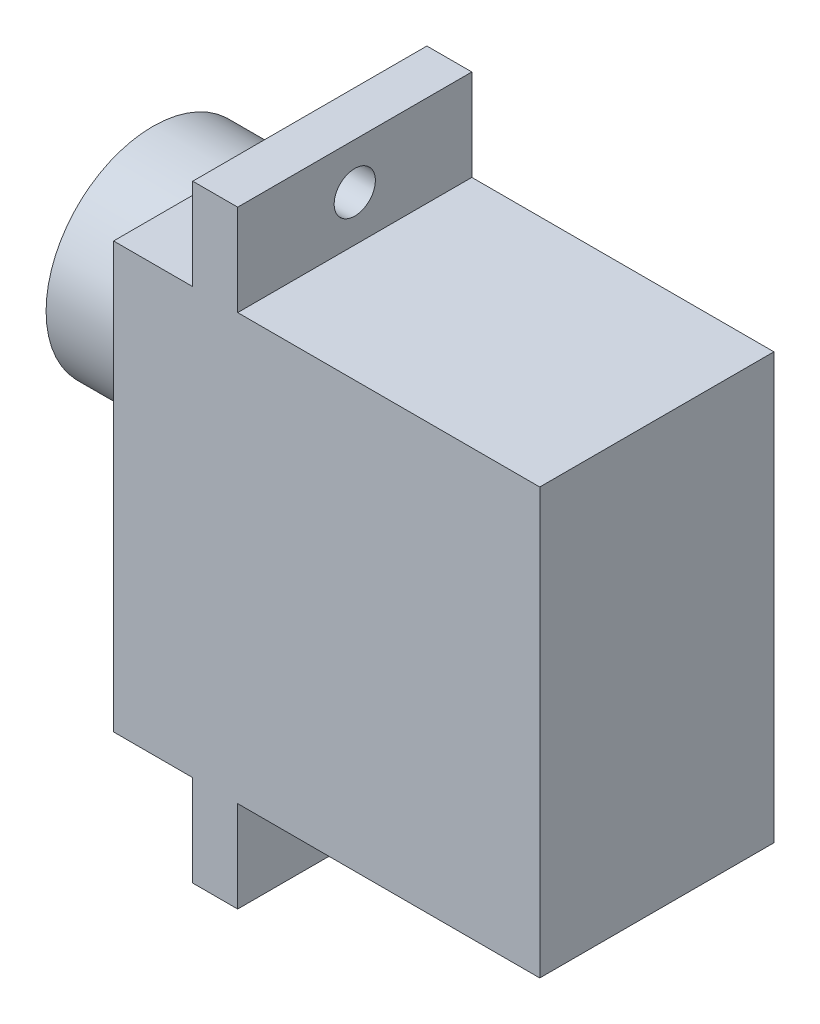
SolidWorks part; units mm, degrees
ref_plane "Front Plane" through (0, 0, 0) normal (0, 0, 1) x (1, 0, 0)
ref_plane "Top Plane" through (0, 0, 0) normal (0, 1, 0) x (1, 0, 0)
ref_plane "Right Plane" through (0, 0, 0) normal (1, 0, 0) x (0, 0, -1)
sketch "Sketch1" plane through (0, 0, 0) normal (0, 0, 1) x (1, 0, 0)
  line L1 (11.375, -11.35) -> (-11.375, -11.35)
  line L2 (11.375, -11.35) -> (11.375, 11.35)
  line L3 (11.375, 11.35) -> (-11.375, 11.35)
  line L4 (-11.375, -11.35) -> (-11.375, 11.35)
  line L5 (11.375, -11.35) -> (-11.375, 11.35) construction
  line L6 (11.375, 11.35) -> (-11.375, -11.35) construction
  point P0 (0, 0)
  dimension "D1" = 22.75
  dimension "D2" = 22.7
extrude "Boss-Extrude1" add sketch "Sketch1" along normal blind 12.5
sketch "Sketch2" plane through (-11.375, 0, 0) normal (-1, 0, 0) x (0, 0, 1)
  line L0 (6.153, 11.8112) -> (6.153, -12.8337) construction
  line L1 (12.5, 11.35) -> (0, 11.35) construction
  circle A0 centre (6.153, 5.65) radius 5.7
  dimension "D1" = 11.4
extrude "Boss-Extrude2" add sketch "Sketch2" along normal blind 4.25
sketch "Sketch3" plane through (-15.625, 0, 0) normal (-1, 0, 0) x (0, 0, 1)
  circle A0 centre (6.153, 5.65) radius 2.3
  dimension "D1" = 4.6
extrude "Cut-Extrude1" cut sketch "Sketch3" against normal blind 2
ref_plane "Plane1" through (11.35, 0, 0) normal (1, 0, 0) x (0, 0, -1)
ref_plane "Plane2" through (-7.15, 0, 0) normal (1, 0, 0) x (0, 0, -1)
sketch "Sketch4" plane through (-7.15, 0, 0) normal (1, 0, 0) x (0, 0, -1)
  line L0 (4.1399, 0) -> (-19.2617, 0) construction
  line L1 (-12.5, 11.35) -> (0, 11.35)
  line L2 (-12.5, 11.35) -> (-12.5, 16.225)
  line L3 (-12.5, 16.225) -> (0, 16.225)
  line L4 (0, 11.35) -> (0, 16.225)
  line L5 (0, -11.35) -> (0, -16.225)
  line L6 (-12.5, -16.225) -> (0, -16.225)
  line L7 (-12.5, -11.35) -> (-12.5, -16.225)
  line L8 (-12.5, -11.35) -> (0, -11.35)
  dimension "D1" = 4.875
extrude "Boss-Extrude3" add sketch "Sketch4" along normal blind 2.4
sketch "Sketch5" plane through (-7.15, 0, 0) normal (-1, 0, 0) x (0, 0, 1)
  line L0 (6.25, 17.3378) -> (6.25, -19.2103) construction
  line L1 (-2.4882, 13.7875) -> (14.0867, 13.7875) construction
  line L2 (-5.2112, 0) -> (17.6459, 0) construction
  circle A0 centre (6.25, 13.7875) radius 1.1
  circle A1 centre (6.25, -13.7875) radius 1.1
  dimension "D1" = 2.2
extrude "Cut-Extrude2" cut sketch "Sketch5" against normal blind 2.4
